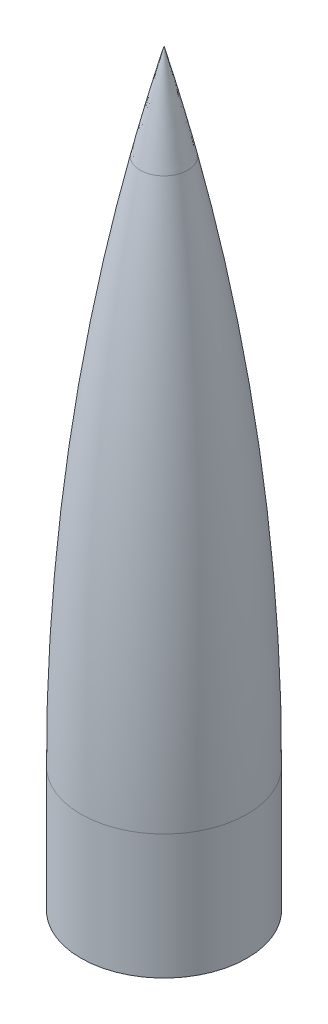
SolidWorks part; units mm, degrees
ref_plane "Front Plane" through (0, 0, 0) normal (0, 0, 1) x (1, 0, 0)
ref_plane "Top Plane" through (0, 0, 0) normal (0, 1, 0) x (1, 0, 0)
ref_plane "Right Plane" through (0, 0, 0) normal (1, 0, 0) x (0, 0, -1)
sketch "Sketch1" plane through (0, 0, 0) normal (0, 0, 1) x (1, 0, 0)
  line L0 (0, 0) -> (0, 457.2) construction
  line L1 (-50.8, 0) -> (-49.53, 0)
  line L2 (-50.8, 0) -> (-50.8, 76.2)
  line L4 (-49.53, 0) -> (-49.53, 76.2)
  line L5 (-13.2665, 398.78) -> (0, 398.78)
  line L6 (0, 457.2) -> (0, 398.78)
  line L7 (-13.2665, 398.78) -> (-14.569, 398.78)
  arc A0 (-50.8, 76.2) -> (0, 457.2) centre (1403.35, 76.2) cw
  arc A1 (-49.53, 76.2) -> (-13.2665, 398.78) centre (1403.35, 76.2) cw
  dimension "D1" = 1.27
  dimension "D2" = 76.2
  dimension "D3" = 50.8
  dimension "D4" = 457.2
  dimension "D5" = 58.42
ref_plane "Plane1" through (0, 457.2, 0) normal (0, 1, 0) x (1, 0, 0)
revolve "Revolve4" add sketch "Sketch1" angle 360 about L0
sketch "Sketch4" plane through (0, 0, 0) normal (0, 0, 1) x (1, 0, 0)
  line L0 (0, 457.2) -> (0, 398.78) construction
  line L1 (0, 457.2) -> (0, 398.78)
  line L3 (14.569, 398.78) -> (-14.569, 398.78) construction
  line L7 (14.569, 398.78) -> (-14.569, 398.78)
  line L8 (0, 398.78) -> (0, 393.4786) construction
  arc A0 (0, 457.2) -> (-50.8, 76.2) centre (1403.35, 76.2) ccw construction
  arc A1 (0, 457.2) -> (-50.8, 76.2) centre (1403.35, 76.2) ccw
revolve "Revolve5" add sketch "Sketch4" angle 360 about L8
